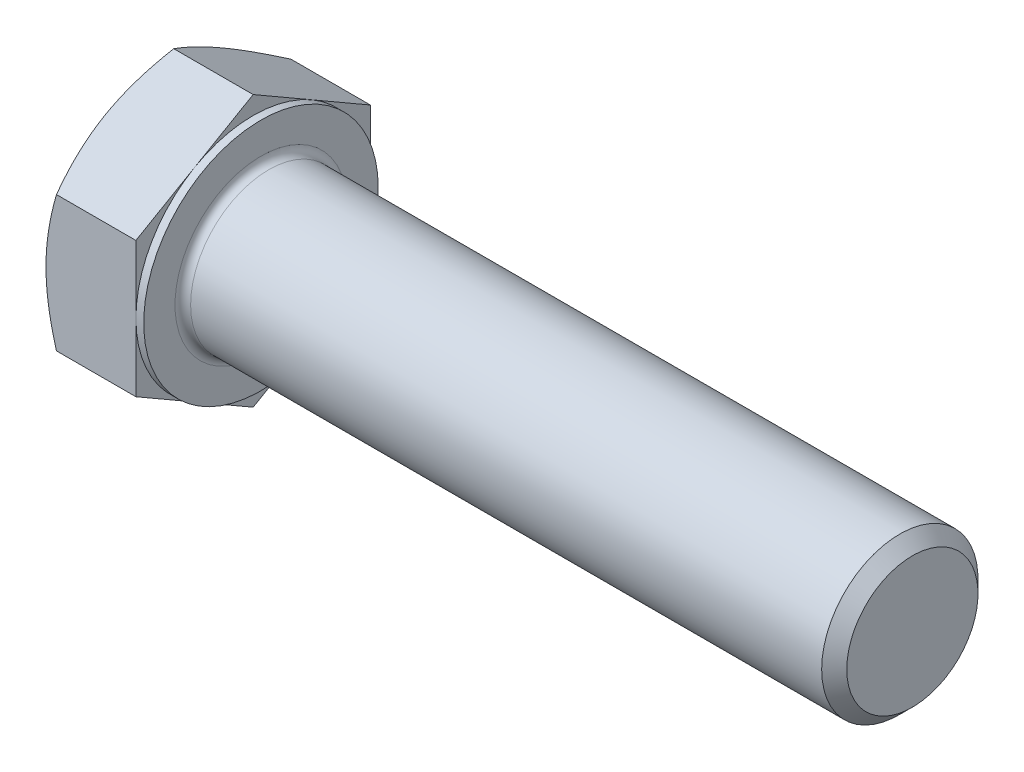
SolidWorks part; units mm, degrees
ref_plane "Plane1" through (0, 0, 0) normal (0, 0, 1) x (1, 0, 0)
ref_plane "Plane2" through (0, 0, 0) normal (0, 1, 0) x (1, 0, 0)
ref_plane "Plane3" through (0, 0, 0) normal (1, 0, 0) x (0, 0, -1)
sketch "Sketch1" plane through (0, 0, 0) normal (1, 0, 0) x (0, 0, -1)
  line L0 (9, 5.1962) -> (9, -5.1962)
  line L1 (-9, 5.1962) -> (-9, -5.1962)
  line L2 (9, -5.1962) -> (0, -10.3923)
  line L3 (0, -10.3923) -> (-9, -5.1962)
  line L4 (9, 5.1962) -> (0, 10.3923)
  line L5 (0, 10.3923) -> (-9, 5.1962)
  dimension "Width_flats" = 18
  dimension "D2" = 120
  dimension "D3" = 9
  dimension "D4" = 9
  dimension "D5" = 9
extrude "BaseHead" add sketch "Sketch1" along normal blind 7.5
sketch "BodySke" plane through (0, 0, 0) normal (0, 0, 1) x (1, 0, 0)
  line L0 (0, 5.1962) -> (0, -5.1962) construction
  line L1 (0, 0) -> (57.5, 0)
  line L2 (0, 0) -> (0, 6)
  line L3 (0, 6) -> (56.536, 6)
  line L4 (57.5, 0) -> (57.5, 5.036)
  line L5 (7.5, 10.3923) -> (7.5, 5.1962) construction
  line L6 (57.5, 5.036) -> (56.536, 6)
  line L7 (0, 0) -> (96.52, 0) construction
  line L8 (57.5, -5.036) -> (56.536, -6) construction
  line L9 (0, -6) -> (56.536, -6) construction
  line L10 (9.25, 15.24) -> (9.25, -1.27) construction
  line L11 (27.5, 15.24) -> (27.5, -1.27) construction
  line L12 (7.5, 5.1962) -> (7.5, -5.1962) construction
  dimension "Length" = 50
  dimension "Body_ch_ang" = 45
  dimension "Diameter" = 12
  dimension "Minor_dia" = 10.072
  dimension "Advance" = 1.75
  dimension "Thread_nom" = 30
revolve "BaseBody" add sketch "BodySke"
cosmetic thread "ThreadCosmetic" [suppressed]
fillet "HeadFillet" radius 0.6 1 edges at (7.5, 0, -6)
sketch "Sketch3" plane through (0, 0, 0) normal (0, 0, 1) x (1, 0, 0)
  line L0 (0, 9) -> (3.6906, 15.3923)
  line L1 (0, 10.3923) -> (0, 5.1962) construction
  line L2 (3.6906, 15.3923) -> (3.6906, 20.3923)
  line L3 (3.6906, 20.3923) -> (-10, 20.3923)
  line L4 (-10, 20.3923) -> (-10, 9)
  line L5 (-10, 9) -> (0, 9)
  line L6 (0, 0) -> (99.06, 0) construction
  line L7 (7.5, 10.3923) -> (0, 10.3923) construction
  dimension "D1" = 9
  dimension "D2" = 5
  dimension "D3" = 10
  dimension "D4" = 5
  dimension "Head_ch_ang" = 30
revolve "HeadChamfer" cut sketch "Sketch3" angle 360 about L6
sketch "Sketch4" plane through (0, 0, 0) normal (0, 0, 1) x (1, 0, 0)
  line L1 (7.5, 10.3923) -> (7.5, 5.1962) construction
  line L2 (7.5, 9) -> (6.9, 9)
  line L3 (7.5, 9) -> (7.5, 20.3923)
  line L4 (7.5, 20.3923) -> (6.9, 20.3923)
  line L5 (0, 0) -> (95.25, 0) construction
  line L6 (0, 0) -> (96.52, 0) construction
  line L7 (6.9, 9) -> (6.9, 20.3923)
  line L8 (7.5, 10.3923) -> (0.8038, 10.3923) construction
  dimension "D1" = 18
  dimension "D2" = 10
  dimension "Bearing_ht" = 0.6
revolve "BearingFace" cut sketch "Sketch4" angle 360 about L5
sketch "ThdSchSke" plane through (0, 0, 0) normal (0, 0, 1) x (1, 0, 0)
  line L0 (27.5, -5.036) -> (26.825, -6)
  line L1 (27.5, -5.036) -> (28.175, -6)
  line L2 (28.175, -6) -> (28.175, -7.5)
  line L3 (-3.175, 0) -> (5.1513, 0) construction
  line L5 (28.175, -7.5) -> (26.825, -7.5)
  line L6 (26.825, -7.5) -> (26.825, -6)
  dimension "Thread_minor" = 10.072
  dimension "Diameter" = 12
  dimension "Start" = 27.5
  dimension "SideAngle" = 55
  dimension "VeeAngle" = 70
  dimension "Overcut" = 15
revolve "ThreadSchematic" [suppressed] cut sketch "ThdSchSke" angle 360 about L3
pattern_linear "ThdSchPat" [suppressed]
equation "\"D3@Sketch1\" = \"Width_flats@Sketch1\" / 2"
equation "\"D4@Sketch1\" = \"D3@Sketch1\""
equation "\"D5@Sketch1\" = \"D4@Sketch1\""
equation "\"Thread_minor@ThreadCosmetic\" = \"Minor_dia@BodySke\""
equation "\"D1@Sketch3\" = \"Width_flats@Sketch1\" / 2"
equation "\"D1@Sketch4\" = \"Width_flats@Sketch1\""
equation "\"Thread_length@ThreadCosmetic\" = ((sgn( (\"Length@BodySke\" - \"Advance@BodySke\" ) - \"Thread_nom@BodySke\" )-1)*( (\"Length@BodySke\" - \"Advance@BodySke\" ) - \"Thread_nom@BodySke\" ))/-2+ \"Thread_nom@BodySke\""
equation "\"Thread_minor@ThdSchSke\" = \"Minor_dia@BodySke\""
equation "\"Diameter@ThdSchSke\" = \"Diameter@BodySke\""
equation "\"Overcut@ThdSchSke\" = \"Diameter@BodySke\" * 1.25"
equation "\"Start@ThdSchSke\" = \"Head_ht@BaseHead\" + \"Length@BodySke\" - \"Thread_length@ThreadCosmetic\"  '---Non-countersunk---"
equation "\"Num_threads@ThdSchPat\" = int( \"Thread_length@ThreadCosmetic\" / \"Advance@BodySke\" + 0.999 )  + 1"
equation "\"Advance@ThdSchPat\" = \"Thread_length@ThreadCosmetic\" /  (\"Num_threads@ThdSchPat\" - 1) 'relax it"
equation "\"Num_threads@ThdSchPat\" = \"Num_threads@ThdSchPat\" - sgn( \"Num_threads@ThdSchPat\" - 1) '---chamfered tips only---"
